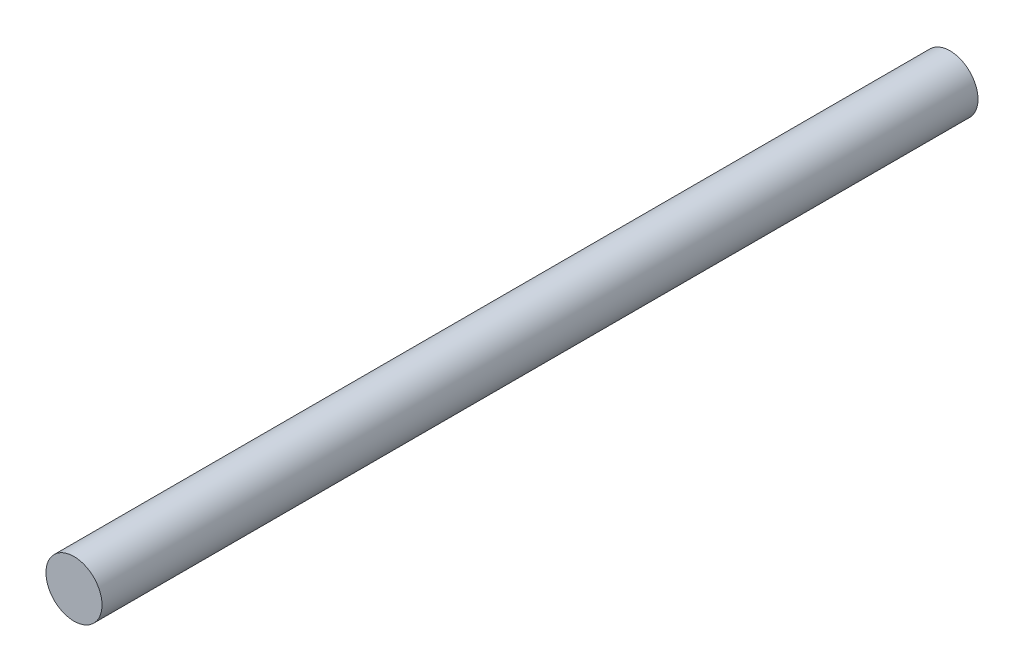
SolidWorks part; units mm, degrees
ref_plane "Front Plane" through (0, 0, 0) normal (0, 0, 1) x (1, 0, 0)
ref_plane "Top Plane" through (0, 0, 0) normal (0, 1, 0) x (1, 0, 0)
ref_plane "Right Plane" through (0, 0, 0) normal (1, 0, 0) x (0, 0, -1)
sketch "Sketch1" plane through (0, 0, 0) normal (0, 0, 1) x (1, 0, 0)
  circle A0 centre (0, 0) radius 1.6
  dimension "D1" = 3.2
extrude "Boss-Extrude1" add sketch "Sketch1" along normal blind 50
